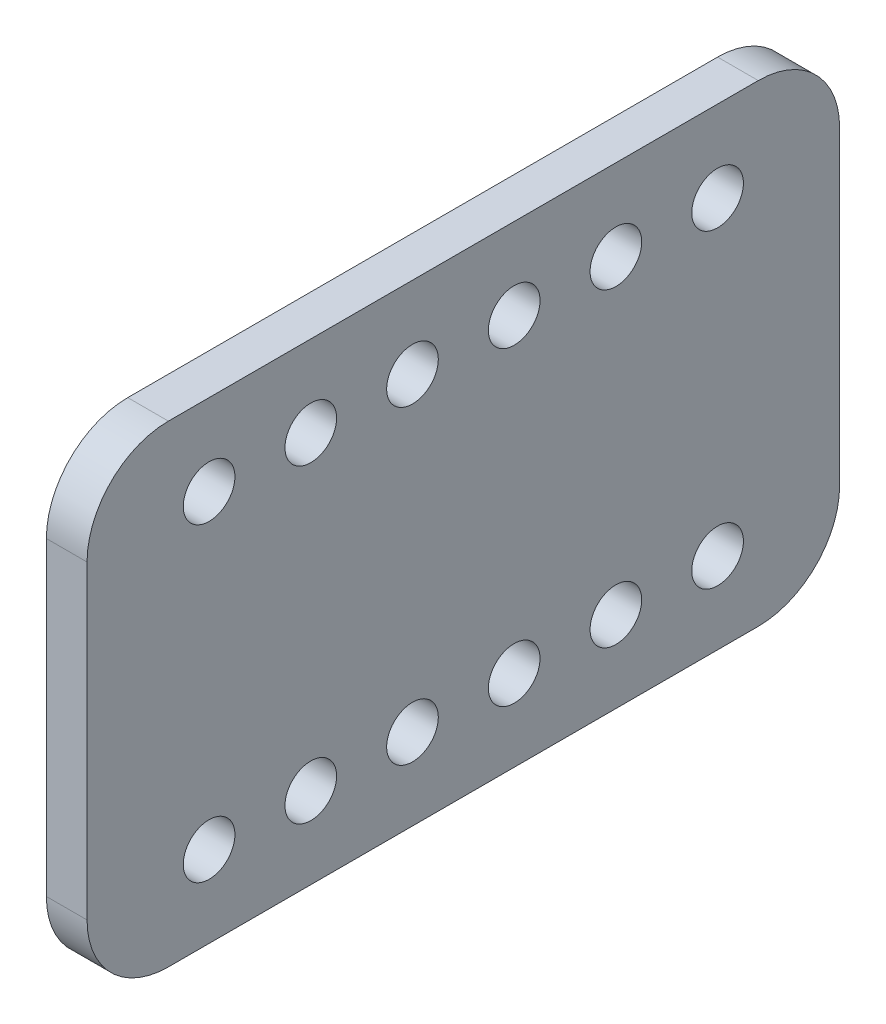
SolidWorks part; units mm, degrees
ref_plane "Front Plane" through (0, 0, 0) normal (0, 0, 1) x (1, 0, 0)
ref_plane "Top Plane" through (0, 0, 0) normal (0, 1, 0) x (1, 0, 0)
ref_plane "Right Plane" through (0, 0, 0) normal (1, 0, 0) x (0, 0, -1)
sketch "Sketch1" plane through (0, 0, 0) normal (1, 0, 0) x (0, 0, -1)
  line L1 (0, 0) -> (18.5, 0)
  line L2 (0, 0) -> (0, 11.62)
  line L3 (0, 11.62) -> (18.5, 11.62)
  line L4 (18.5, 0) -> (18.5, 11.62)
  circle A0 centre (15.5, 9.62) radius 0.635
  circle A1 centre (13, 9.62) radius 0.635
  circle A2 centre (10.5, 9.62) radius 0.635
  circle A3 centre (8, 9.62) radius 0.635
  circle A4 centre (5.5, 9.62) radius 0.635
  circle A5 centre (3, 9.62) radius 0.635
  circle A6 centre (13, 2) radius 0.635
  circle A7 centre (10.5, 2) radius 0.635
  circle A8 centre (8, 2) radius 0.635
  circle A9 centre (5.5, 2) radius 0.635
  circle A10 centre (3, 2) radius 0.635
  circle A11 centre (15.5, 2) radius 0.635
  dimension "D1" = 1.27
  dimension "D4" = 3
  dimension "D5" = 3
  dimension "D7" = 2
  dimension "D8" = 7.62
  dimension "D6" = 2
  dimension "D2" = 6
  dimension "D3" = 2
extrude "Boss-Extrude1" add sketch "Sketch1" along normal blind 1
fillet "Fillet1" radius 2 4 edges at (0.5, 0, 0) (0.5, 11.62, 0) (0.5, 0, -18.5) (0.5, 11.62, -18.5)
